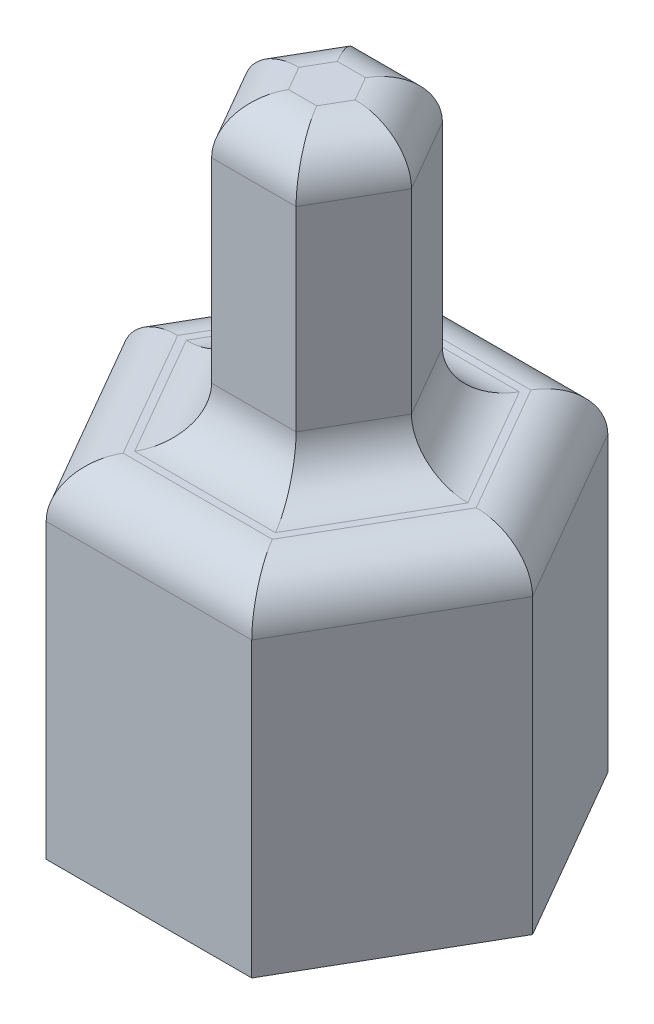
SolidWorks part; units mm, degrees
ref_plane "Front Plane" through (0, 0, 0) normal (0, 0, 1) x (1, 0, 0)
ref_plane "Top Plane" through (0, 0, 0) normal (0, 1, 0) x (1, 0, 0)
ref_plane "Right Plane" through (0, 0, 0) normal (1, 0, 0) x (0, 0, -1)
sketch "Sketch1" plane through (0, 0, 0) normal (0, 1, 0) x (1, 0, 0)
  line L1 (7.7723, 0) -> (3.8861, 6.731)
  line L2 (3.8861, 6.731) -> (-3.8861, 6.731)
  line L3 (-3.8861, 6.731) -> (-7.7723, 0)
  line L4 (-7.7723, 0) -> (-3.8861, -6.731)
  line L5 (-3.8861, -6.731) -> (3.8861, -6.731)
  line L6 (3.8861, -6.731) -> (7.7723, 0)
  line L7 (10.7052, 0) -> (5.3526, 9.271)
  line L8 (5.3526, 9.271) -> (-5.3526, 9.271)
  line L9 (-5.3526, 9.271) -> (-10.7052, 0)
  line L10 (-10.7052, 0) -> (-5.3526, -9.271)
  line L11 (-5.3526, -9.271) -> (5.3526, -9.271)
  line L12 (5.3526, -9.271) -> (10.7052, 0)
  circle A0 centre (0, 0) radius 6.731 construction
  circle A1 centre (0, 0) radius 9.271 construction
  dimension "D1" = 13.462
  dimension "D2" = 18.542
extrude "Boss-Extrude1" add sketch "Sketch1" along normal blind 15.24
sketch "Sketch2" plane through (0, 15.24, 0) normal (0, 1, 0) x (1, 0, 0)
  line L1 (10.7052, 0) -> (5.3526, 9.271)
  line L2 (5.3526, 9.271) -> (-5.3526, 9.271)
  line L3 (-5.3526, 9.271) -> (-10.7052, 0)
  line L4 (-10.7052, 0) -> (-5.3526, -9.271)
  line L5 (-5.3526, -9.271) -> (5.3526, -9.271)
  line L6 (5.3526, -9.271) -> (10.7052, 0)
  circle A0 centre (0, 0) radius 9.271 construction
  dimension "D1" = 18.542
extrude "Boss-Extrude2" add sketch "Sketch2" along normal blind 2.54
sketch "Sketch3" plane through (0, 17.78, 0) normal (0, 1, 0) x (1, 0, 0)
  line L1 (4.3994, 0) -> (2.1997, 3.81)
  line L2 (2.1997, 3.81) -> (-2.1997, 3.81)
  line L3 (-2.1997, 3.81) -> (-4.3994, 0)
  line L4 (-4.3994, 0) -> (-2.1997, -3.81)
  line L5 (-2.1997, -3.81) -> (2.1997, -3.81)
  line L6 (2.1997, -3.81) -> (4.3994, 0)
  circle A0 centre (0, 0) radius 3.81 construction
  dimension "D1" = 7.62
extrude "Boss-Extrude3" add sketch "Sketch3" along normal blind 15.24
sketch "Sketch8" plane through (0, 0, 0) normal (0, -1, 0) x (1, 0, 0)
  line L0 (3.8861, 6.731) -> (7.7723, 0) construction
  line L1 (3.8861, 6.731) -> (7.7723, 0)
  spline S0 degree 2 poles (3.8861, 6.731) (7.589, 4.3815) (7.7723, 0) knots 0 0 0 1 1 1
  dimension "D1" = 1.016
extrude "Cut-Extrude3" cut sketch "Sketch8" against normal blind 15.24
fillet "Fillet9" radius 2.54 12 edges at (0, 33.02, 3.81) (-3.2996, 33.02, 1.905) (-3.2996, 33.02, -1.905) (0, 33.02, -3.81) (3.2996, 33.02, -1.905) (3.2996, 33.02, 1.905) (0, 17.78, -3.81) (-3.2996, 17.78, -1.905) (-3.2996, 17.78, 1.905) (0, 17.78, 3.81) (3.2996, 17.78, 1.905) (3.2996, 17.78, -1.905)
sketch "Sketch9" plane through (0, 0, 0) normal (0, -1, 0) x (1, 0, 0)
  line L0 (-3.8861, -6.731) -> (-7.7723, 0) construction
  line L1 (-7.7723, 0) -> (-3.8861, -6.731)
  spline S0 degree 2 poles (-7.7723, 0) (-7.589, -4.3815) (-3.8861, -6.731) knots 0 0 0 1 1 1
  dimension "D1" = 1.016
extrude "Cut-Extrude4" cut sketch "Sketch9" against normal blind 15.24
fillet "Fillet1" radius 2.54 6 edges at (0, 17.78, 9.271) (-8.0289, 17.78, 4.6355) (-8.0289, 17.78, -4.6355) (0, 17.78, -9.271) (8.0289, 17.78, -4.6355) (8.0289, 17.78, 4.6355)
